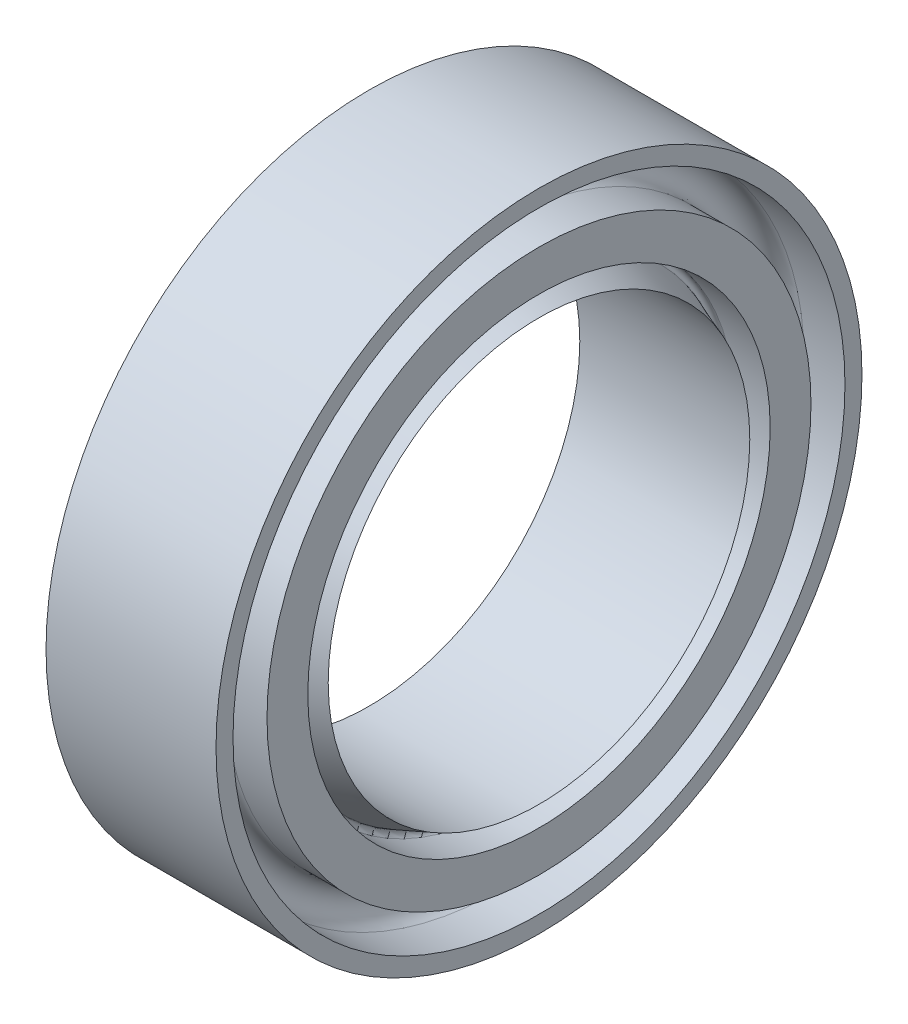
SolidWorks part; units mm, degrees
ref_plane "Plan1" through (0, 0, 0) normal (0, 0, 1) x (1, 0, 0)
ref_plane "Plan2" through (0, 0, 0) normal (0, 1, 0) x (1, 0, 0)
ref_plane "Plan3" through (0, 0, 0) normal (1, 0, 0) x (0, 0, -1)
sketch "Esquisse1" plane through (0, 0, 0) normal (0, 0, 1) x (1, 0, 0)
  line L0 (0, 31) -> (25, 31)
  line L1 (0, 40) -> (6, 40)
  line L2 (19.5818, 33.0318) -> (25, 31)
  line L3 (6, 45) -> (0, 45)
  line L4 (0, 45) -> (0, 47.5)
  line L5 (0, 47.5) -> (25, 47.5)
  line L6 (25, 34) -> (19.7573, 34)
  line L7 (0, 40) -> (0, 34)
  line L8 (0, 34) -> (5.2427, 34)
  line L9 (25, 40) -> (25, 34)
  line L10 (5.4182, 33.0318) -> (0, 31)
  line L11 (25, 40) -> (19, 40)
  line L12 (12.5, 99.0137) -> (12.5, 37.8897) construction
  line L13 (19, 45) -> (25, 45)
  line L14 (25, 45) -> (25, 47.5)
  line L15 (0, 0) -> (41.0817, 0) construction
  arc A0 (6, 45) -> (6, 40) centre (6, 42.5) cw
  arc A1 (19, 45) -> (19, 40) centre (19, 42.5) ccw
  arc A2 (5.4182, 33.0318) -> (5.2427, 34) centre (5.2427, 33.5) ccw
  arc A3 (19.7573, 34) -> (19.5818, 33.0318) centre (19.7573, 33.5) ccw
  point P11 (12.5, 31)
  point P23 (12.5, 47.5)
  point P25 (8, 34)
  point P28 (17, 34)
  dimension "D9" = 0.5
  dimension "D1" = 12.5
  dimension "D2" = 31
  dimension "D3" = 3
  dimension "D4" = 8
  dimension "D5" = 6
  dimension "D6" = 5
  dimension "D7" = 6
  dimension "D8" = 47.5
revolve "corps" add sketch "Esquisse1" angle 360 about L15
